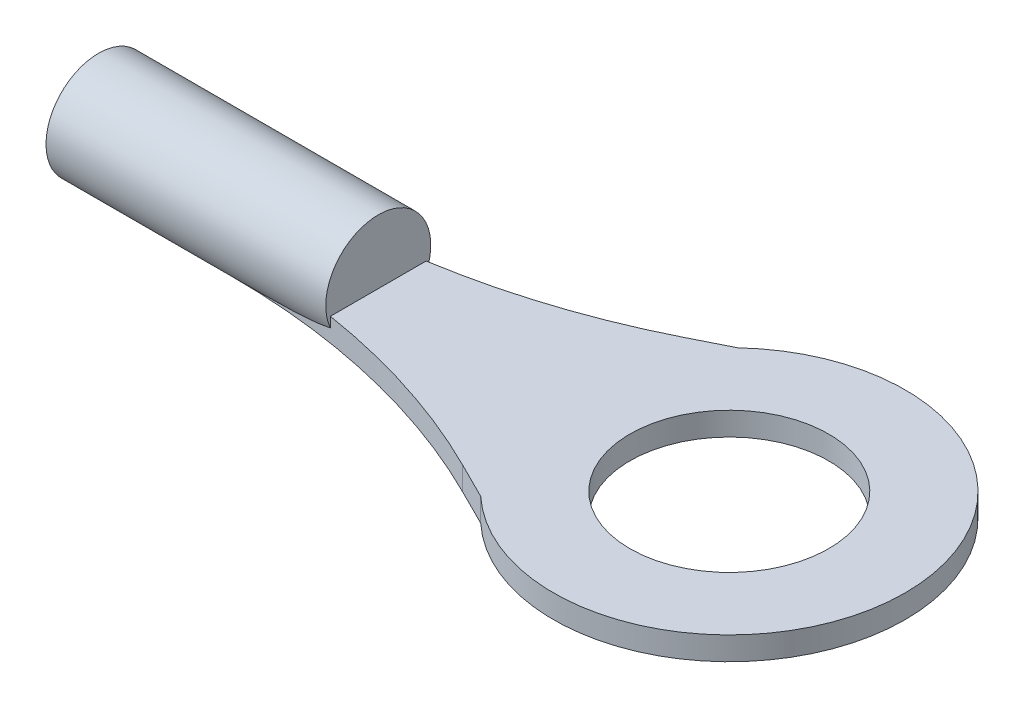
SolidWorks part; units mm, degrees
ref_plane "Front Plane" through (0, 0, 0) normal (0, 0, 1) x (1, 0, 0)
ref_plane "Top Plane" through (0, 0, 0) normal (0, 1, 0) x (1, 0, 0)
ref_plane "Right Plane" through (0, 0, 0) normal (1, 0, 0) x (0, 0, -1)
sketch "Sketch1" plane through (0, 0, 0) normal (0, 1, 0) x (1, 0, 0)
  line L1 (-21.3614, 0) -> (-21.3614, 1.3335)
  line L2 (-21.3614, 0) -> (-21.3614, -1.3335)
  line L3 (-21.3614, 1.3335) -> (-15.5033, 1.3335)
  line L4 (-21.3614, -1.3335) -> (-15.5033, -1.3335)
  line L6 (-4.0634, 4.3551) -> (-5.2822, 3.7458)
  line L8 (-5.2822, -3.7458) -> (-4.0634, -4.3551)
  circle A0 centre (0, 0) radius 3.3655
  arc A1 (-4.0634, -4.3551) -> (-4.0634, 4.3551) centre (0, 0) ccw
  arc A2 (-15.5033, -1.3335) -> (-5.2822, -3.7458) centre (-15.5033, -24.1935) cw
  arc A3 (-15.5033, 1.3335) -> (-5.2822, 3.7458) centre (-15.5033, 24.1935) ccw
  dimension "D1" = 6.731
  dimension "D2" = 11.9126
  dimension "D6" = 22.86
  dimension "D3" = 21.3614
  dimension "D4" = 1.3335
  dimension "D5" = 1.3335
extrude "Boss-Extrude1" add sketch "Sketch1" along normal blind 0.7874
sketch "Sketch2" plane through (-21.3614, 0, 0) normal (-1, 0, 0) x (0, 0, 1)
  circle A0 centre (0, 1.176) radius 1.778
  dimension "D1" = 3.556
extrude "Boss-Extrude2" add sketch "Sketch2" against normal blind 9.4742
sketch "Sketch3" plane through (-21.3614, 0, 0) normal (-1, 0, 0) x (0, 0, 1)
  circle A0 centre (0, 1.176) radius 1.3366
extrude "Cut-Extrude1" cut sketch "Sketch3" against normal blind 4.3942
